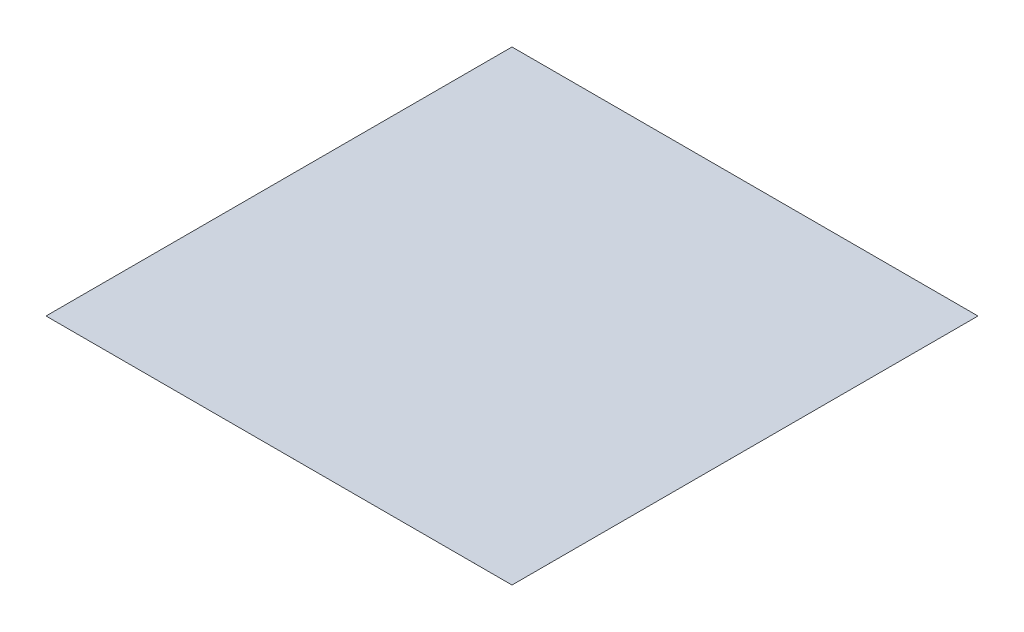
SolidWorks part; units mm, degrees
ref_plane "前视基准面" through (0, 0, 0) normal (0, 0, 1) x (1, 0, 0)
ref_plane "上视基准面" through (0, 0, 0) normal (0, 1, 0) x (1, 0, 0)
ref_plane "右视基准面" through (0, 0, 0) normal (1, 0, 0) x (0, 0, -1)
sketch "草图1" plane through (0, 0, 0) normal (0, 1, 0) x (1, 0, 0)
  line L1 (-325, 325) -> (325, 325)
  line L2 (-325, 325) -> (-325, -325)
  line L3 (-325, -325) -> (325, -325)
  line L4 (325, 325) -> (325, -325)
  line L5 (-325, 325) -> (325, -325) construction
  line L6 (-325, -325) -> (325, 325) construction
  point P0 (0, 0)
  dimension "D1" = 650
extrude "凸台-拉伸1" add sketch "草图1" along normal blind 0.001
